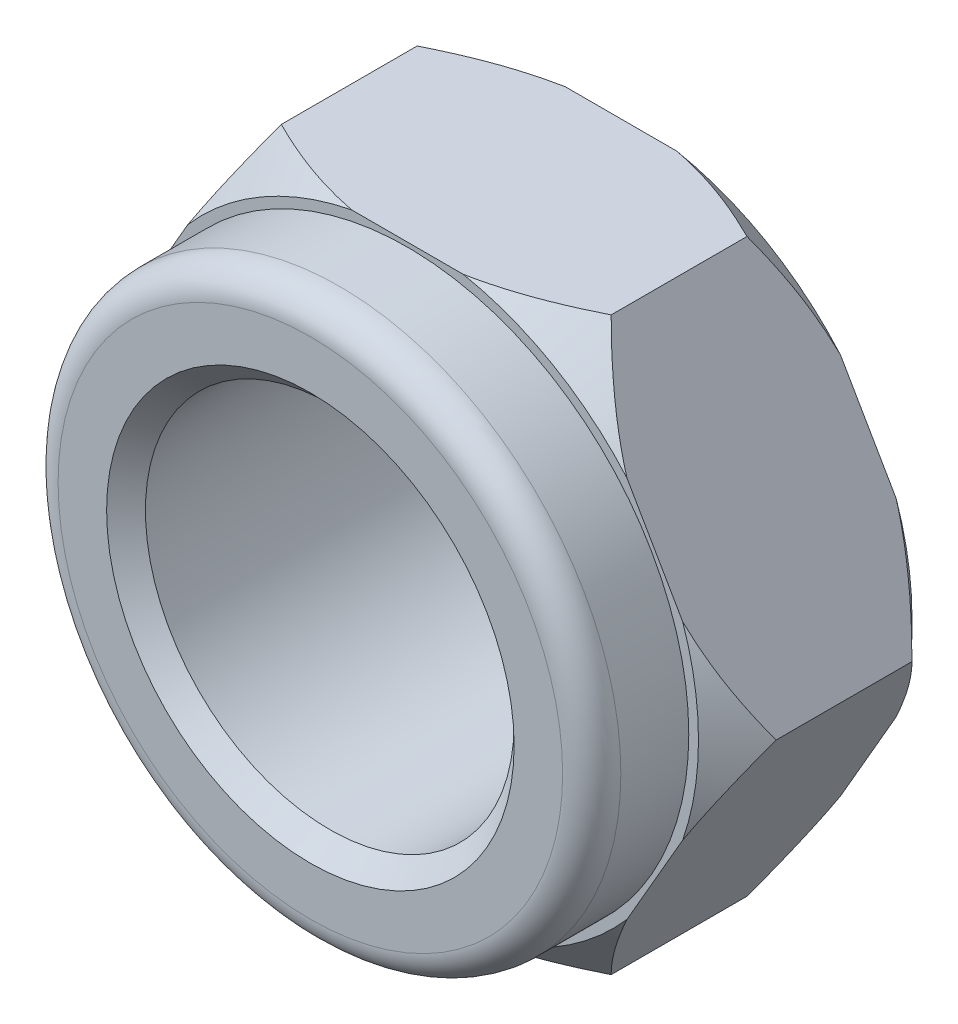
SolidWorks part; units mm, degrees
ref_plane "Plan1" through (0, 0, 0) normal (0, 0, 1) x (1, 0, 0)
ref_plane "Plan2" through (0, 0, 0) normal (0, 1, 0) x (1, 0, 0)
ref_plane "Plan3" through (0, 0, 0) normal (1, 0, 0) x (0, 0, -1)
sketch "Esquisse1" plane through (0, 0, 0) normal (0, 0, 1) x (1, 0, 0)
  circle A0 centre (0, 0) radius 17
  dimension "D1" = 34
extrude "corps de manoeuvre" add sketch "Esquisse1" along normal blind 11
sketch "Esquisse2" plane through (0, 0, 11) normal (0, 0, 1) x (1, 0, 0)
  circle A0 centre (0, 0) radius 14.5
  dimension "D1" = 29
extrude "organe de frein" add sketch "Esquisse2" along normal blind 5
sketch "Esquisse3" plane through (0, 0, 16) normal (0, 0, 1) x (1, 0, 0)
  circle A0 centre (0, 0) radius 9.5
  dimension "D1" = 19
extrude "perçage" cut sketch "Esquisse3" against normal through all
chamfer "Chanfrein de manoeuvre" distance 2 angle 45
sketch "Hexagon - inscribed1" plane through (1.7782, 13.1024, 0) normal (0, 0, -1) x (-1, 0, 0)
  line L0 (18.7782, -13.1024) -> (10.2782, 1.6201)
  line L1 (10.2782, 1.6201) -> (-6.7218, 1.6201)
  line L2 (-6.7218, 1.6201) -> (-15.2218, -13.1024)
  line L3 (-15.2218, -13.1024) -> (-6.7218, -27.8248)
  line L4 (-6.7218, -27.8248) -> (10.2782, -27.8248)
  line L5 (10.2782, -27.8248) -> (18.7782, -13.1024)
  circle A0 centre (1.7782, -13.1024) radius 17 construction
  circle A1 centre (1.7782, -13.1024) radius 17 construction
extrude "manoeuvre" cut sketch "Hexagon - inscribed1" against normal through all flip side to cut
fillet "Congé1" radius 1.5
chamfer "Chanfrein2" distance 1 angle 45
